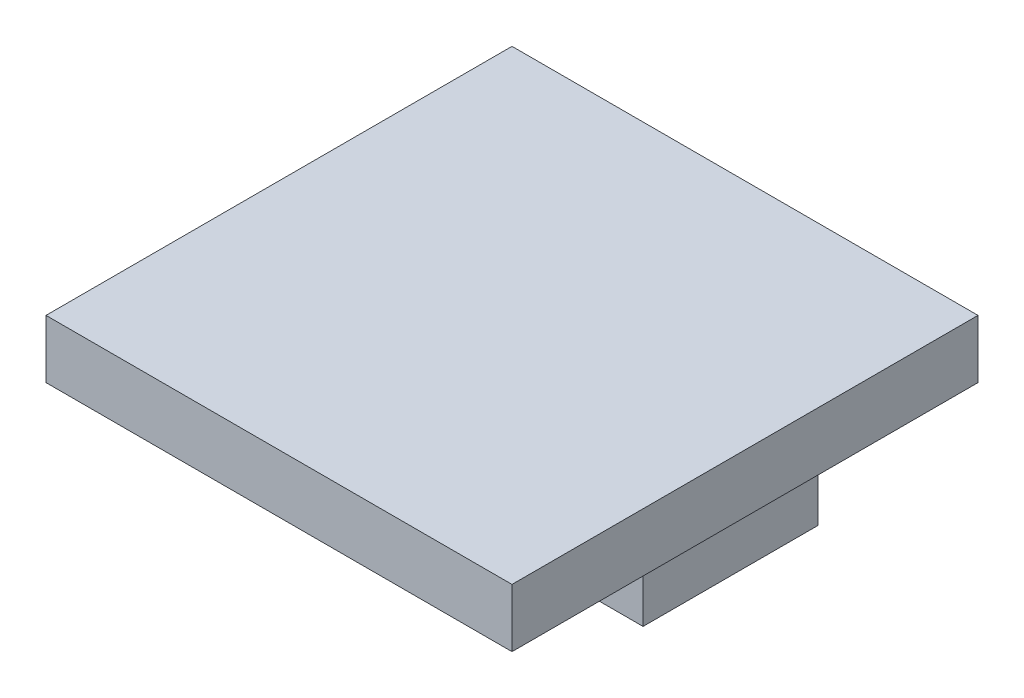
SolidWorks part; units mm, degrees
ref_plane "Front Plane" through (0, 0, 0) normal (0, 0, 1) x (1, 0, 0)
ref_plane "Top Plane" through (0, 0, 0) normal (0, 1, 0) x (1, 0, 0)
ref_plane "Right Plane" through (0, 0, 0) normal (1, 0, 0) x (0, 0, -1)
sketch "Sketch1" plane through (0, 0, 0) normal (0, 1, 0) x (1, 0, 0)
  line L1 (12.5, -6) -> (-12.5, -6)
  line L2 (12.5, -6) -> (12.5, 6)
  line L3 (12.5, 6) -> (-12.5, 6)
  line L4 (-12.5, -6) -> (-12.5, 6)
  line L5 (12.5, -6) -> (-12.5, 6) construction
  line L6 (12.5, 6) -> (-12.5, -6) construction
  point P0 (0, 0)
  dimension "D1" = 12
  dimension "D2" = 25
extrude "Boss-Extrude1" add sketch "Sketch1" along normal blind 4
sketch "Sketch3" plane through (0, 4, 0) normal (0, 1, 0) x (1, 0, 0)
  line L1 (13.5, 16) -> (-18.5, 16)
  line L2 (13.5, 16) -> (13.5, -16)
  line L3 (13.5, -16) -> (-18.5, -16)
  line L4 (-18.5, 16) -> (-18.5, -16)
  dimension "D1" = 32
  dimension "D2" = 32
  dimension "D3" = 16
  dimension "D4" = 13.5
extrude "Boss-Extrude3" add sketch "Sketch3" along normal blind 4
